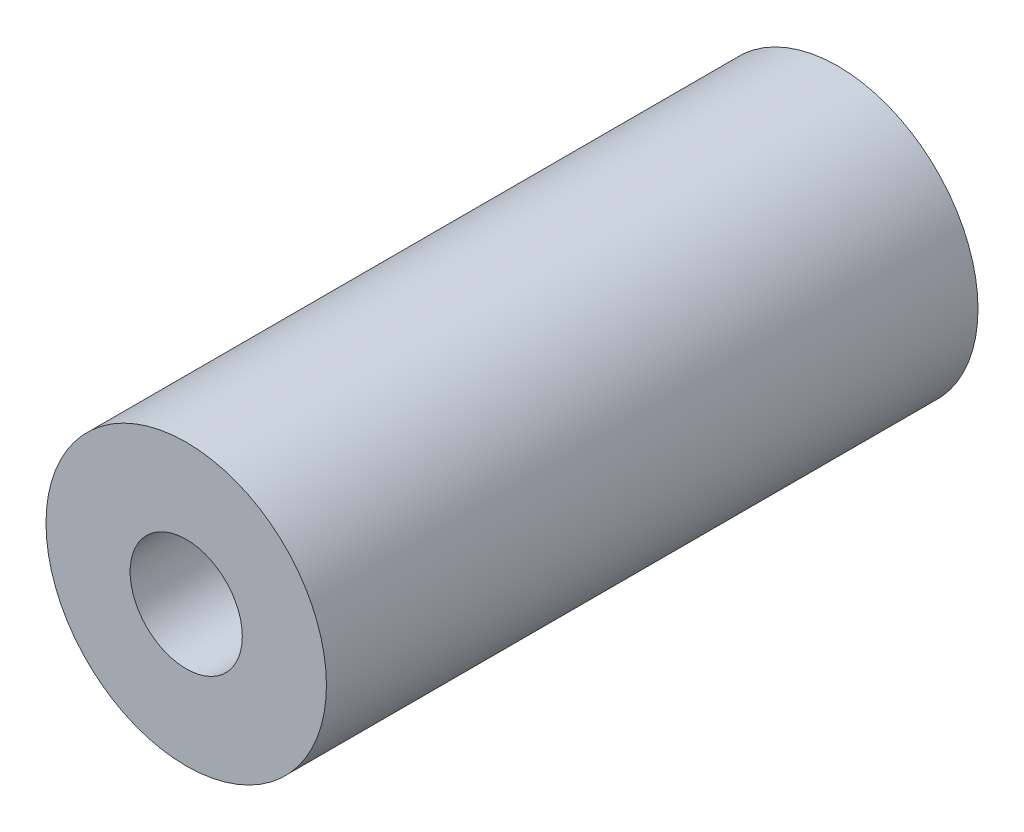
SolidWorks part; units mm, degrees
ref_plane "Alzado" through (0, 0, 0) normal (0, 0, 1) x (1, 0, 0)
ref_plane "Planta" through (0, 0, 0) normal (0, 1, 0) x (1, 0, 0)
ref_plane "Vista lateral" through (0, 0, 0) normal (1, 0, 0) x (0, 0, -1)
sketch "Croquis1" plane through (0, 0, 0) normal (0, 0, 1) x (1, 0, 0)
  circle A0 centre (0, 0) radius 4.25
  circle A1 centre (0, 0) radius 1.7
  dimension "D1" = 8.5
  dimension "D2" = 3.4
extrude "Saliente-Extruir1" add sketch "Croquis1" along normal blind 19.75
